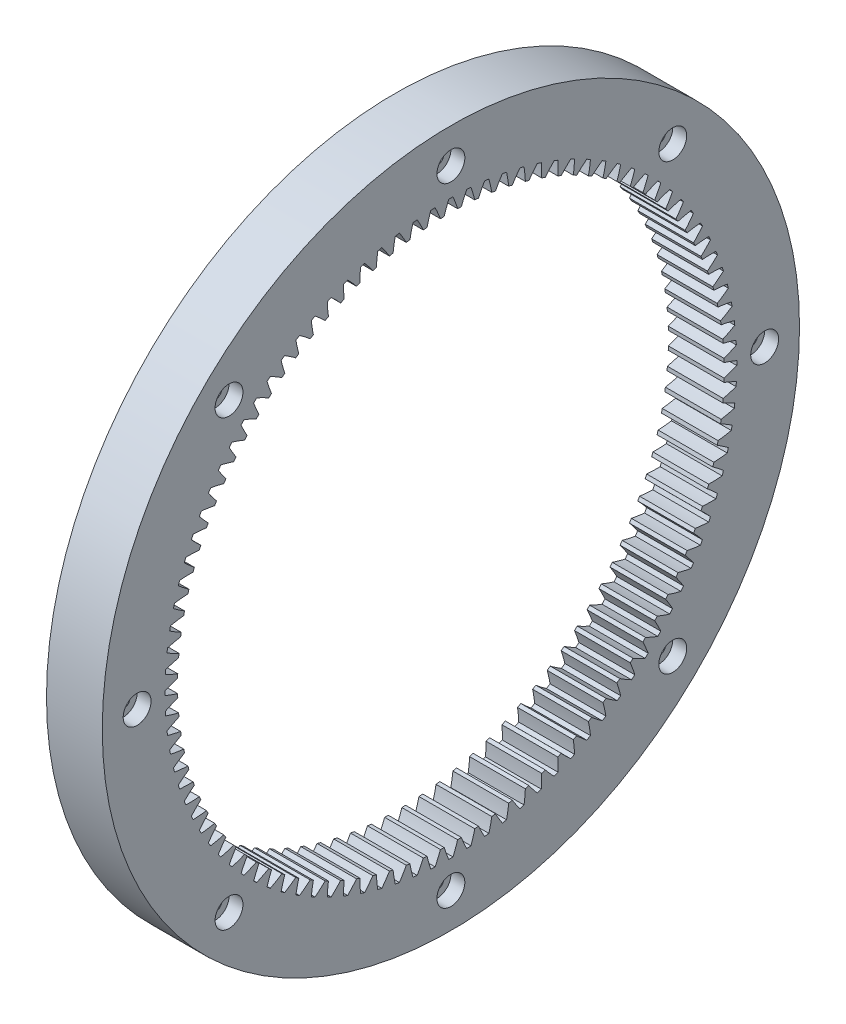
SolidWorks part; units mm, degrees
ref_plane "Front Plane" through (0, 0, 0) normal (0, 0, 1) x (1, 0, 0)
ref_plane "Top Plane" through (0, 0, 0) normal (0, 1, 0) x (1, 0, 0)
ref_plane "Right Plane" through (0, 0, 0) normal (1, 0, 0) x (0, 0, -1)
ref_plane "Plane1" through (-19.2805, 0, 0) normal (-1, 0, 0) x (0, -1, 0)
sketch "Sketch1" plane through (-19.2805, 0, 0) normal (-1, 0, 0) x (0, -1, 0)
  circle A0 centre (2.1716, 9.011) radius 125
  arc A1 (-100.1723, 3.3383) -> (-95.7567, 5.2635) centre (-78.005, -41.4792) cw
  arc A2 (-95.7567, 5.2635) -> (-95.7988, 6.6021) centre (2.1716, 9.011) cw
  arc A3 (-95.7988, 6.6021) -> (-100.3265, 8.2462) centre (-81.0171, 54.3672) cw
  arc A4 (-100.3265, 8.2462) -> (-100.3265, 9.7757) centre (2.1716, 9.011) cw
  arc A5 (-100.3265, 9.7757) -> (-95.7988, 11.4198) centre (-81.0171, -36.3453) cw
  arc A6 (-95.7988, 11.4198) -> (-95.7567, 12.7585) centre (2.1716, 9.011) cw
  arc A7 (-95.7567, 12.7585) -> (-100.1723, 14.6836) centre (-78.005, 59.5012) cw
  arc A8 (-100.1723, 14.6836) -> (-100.0763, 16.2101) centre (2.1716, 9.011) cw
  arc A9 (-100.0763, 16.2101) -> (-95.4542, 17.5667) centre (-83.7009, -31.0323) cw
  arc A10 (-95.4542, 17.5667) -> (-95.3282, 18.9001) centre (2.1716, 9.011) cw
  arc A11 (-95.3282, 18.9001) -> (-99.6142, 21.0987) centre (-74.6765, 64.4359) cw
  arc A12 (-99.6142, 21.0987) -> (-99.4225, 22.6161) centre (2.1716, 9.011) cw
  arc A13 (-99.4225, 22.6161) -> (-94.7244, 23.6798) centre (-86.0458, -25.5613) cw
  arc A14 (-94.7244, 23.6798) -> (-94.5148, 25.0026) centre (2.1716, 9.011) cw
  arc A15 (-94.5148, 25.0026) -> (-98.6543, 27.466) centre (-71.0447, 69.1518) cw
  arc A16 (-98.6543, 27.466) -> (-98.3677, 28.9684) centre (2.1716, 9.011) cw
  arc A17 (-98.3677, 28.9684) -> (-93.6121, 29.735) centre (-88.0425, -19.9539) cw
  arc A18 (-93.6121, 29.735) -> (-93.3199, 31.0421) centre (2.1716, 9.011) cw
  arc A19 (-93.3199, 31.0421) -> (-97.2966, 33.7605) centre (-67.1239, 73.6304) cw
  arc A20 (-97.2966, 33.7605) -> (-96.9162, 35.242) centre (2.1716, 9.011) cw
  arc A21 (-96.9162, 35.242) -> (-92.1218, 35.7084) centre (-89.6832, -14.2321) cw
  arc A22 (-92.1218, 35.7084) -> (-91.7481, 36.9945) centre (2.1716, 9.011) cw
  arc A23 (-91.7481, 36.9945) -> (-95.5462, 39.9573) centre (-62.9297, 77.854) cw
  arc A24 (-95.5462, 39.9573) -> (-95.0736, 41.412) centre (2.1716, 9.011) cw
  arc A25 (-95.0736, 41.412) -> (-90.2594, 41.5764) centre (-90.9614, -8.4186) cw
  arc A26 (-90.2594, 41.5764) -> (-89.8057, 42.8366) centre (2.1716, 9.011) cw
  arc A27 (-89.8057, 42.8366) -> (-93.4103, 46.032) centre (-58.4786, 81.8059) cw
  arc A28 (-93.4103, 46.032) -> (-92.8472, 47.4541) centre (2.1716, 9.011) cw
  arc A29 (-92.8472, 47.4541) -> (-88.0322, 47.316) centre (-91.872, -2.5364) cw
  arc A30 (-88.0322, 47.316) -> (-87.5003, 48.5452) centre (2.1716, 9.011) cw
  arc A31 (-87.5003, 48.5452) -> (-90.8971, 51.9606) centre (-53.788, 85.4705) cw
  arc A32 (-90.8971, 51.9606) -> (-90.2459, 53.3445) centre (2.1716, 9.011) cw
  arc A33 (-90.2459, 53.3445) -> (-85.449, 52.9043) centre (-92.4115, 3.3915) cw
  arc A34 (-85.449, 52.9043) -> (-84.841, 54.0977) centre (2.1716, 9.011) cw
  arc A35 (-84.841, 54.0977) -> (-88.0166, 57.7197) centre (-48.8767, 88.8334) cw
  arc A36 (-88.0166, 57.7197) -> (-87.2798, 59.06) centre (2.1716, 9.011) cw
  arc A37 (-87.2798, 59.06) -> (-82.52, 58.3195) centre (-92.5777, 9.3415) cw
  arc A38 (-82.52, 58.3195) -> (-81.8383, 59.4723) centre (2.1716, 9.011) cw
  arc A39 (-81.8383, 59.4723) -> (-84.7802, 63.2865) centre (-43.7639, 91.8812) cw
  arc A40 (-84.7802, 63.2865) -> (-83.9607, 64.5779) centre (2.1716, 9.011) cw
  arc A41 (-83.9607, 64.5779) -> (-79.2568, 63.54) centre (-92.37, 15.2902) cw
  arc A42 (-79.2568, 63.54) -> (-78.504, 64.6477) centre (2.1716, 9.011) cw
  arc A43 (-78.504, 64.6477) -> (-81.2007, 68.6392) centre (-38.4698, 94.602) cw
  arc A44 (-81.2007, 68.6392) -> (-80.3016, 69.8766) centre (2.1716, 9.011) cw
  arc A45 (-80.3016, 69.8766) -> (-75.6722, 68.5453) centre (-91.7892, 21.2141) cw
  arc A46 (-75.6722, 68.5453) -> (-74.8513, 69.6036) centre (2.1716, 9.011) cw
  arc A47 (-74.8513, 69.6036) -> (-77.292, 73.7565) centre (-33.0152, 96.985) cw
  arc A48 (-77.292, 73.7565) -> (-76.3171, 74.935) centre (2.1716, 9.011) cw
  arc A49 (-76.3171, 74.935) -> (-71.7804, 73.3157) centre (-90.8375, 27.0899) cw
  arc A50 (-71.7804, 73.3157) -> (-70.8947, 74.3204) centre (2.1716, 9.011) cw
  arc A51 (-70.8947, 74.3204) -> (-73.0698, 78.6183) centre (-27.4219, 99.0208) cw
  arc A52 (-73.0698, 78.6183) -> (-72.0228, 79.7333) centre (2.1716, 9.011) cw
  arc A53 (-72.0228, 79.7333) -> (-67.5968, 77.8323) centre (-89.5188, 32.8943) cw
  arc A54 (-67.5968, 77.8323) -> (-66.6497, 78.7794) centre (2.1716, 9.011) cw
  arc A55 (-66.6497, 78.7794) -> (-68.5507, 83.2054) centre (-21.7117, 100.7014) cw
  arc A56 (-68.5507, 83.2054) -> (-67.4357, 84.2524) centre (2.1716, 9.011) cw
  arc A57 (-67.4357, 84.2524) -> (-63.1378, 82.0773) centre (-87.8383, 38.6045) cw
  arc A58 (-63.1378, 82.0773) -> (-62.1331, 82.963) centre (2.1716, 9.011) cw
  arc A59 (-62.1331, 82.963) -> (-63.7524, 87.4997) centre (-15.9073, 102.0201) cw
  arc A60 (-63.7524, 87.4997) -> (-62.5739, 88.4746) centre (2.1716, 9.011) cw
  arc A61 (-62.5739, 88.4746) -> (-58.421, 86.0339) centre (-85.8024, 44.1978) cw
  arc A62 (-58.421, 86.0339) -> (-57.3627, 86.8548) centre (2.1716, 9.011) cw
  arc A63 (-57.3627, 86.8548) -> (-58.694, 91.4842) centre (-10.0315, 102.9718) cw
  arc A64 (-58.694, 91.4842) -> (-57.4566, 92.3832) centre (2.1716, 9.011) cw
  arc A65 (-57.4566, 92.3832) -> (-53.4652, 89.6866) centre (-83.4195, 49.6523) cw
  arc A66 (-53.4652, 89.6866) -> (-52.3574, 90.4394) centre (2.1716, 9.011) cw
  arc A67 (-52.3574, 90.4394) -> (-53.3954, 95.1432) centre (-4.1076, 103.5526) cw
  arc A68 (-53.3954, 95.1432) -> (-52.1039, 95.9628) centre (2.1716, 9.011) cw
  arc A69 (-52.1039, 95.9628) -> (-48.2897, 93.0208) centre (-80.6987, 54.9464) cw
  arc A70 (-48.2897, 93.0208) -> (-47.1369, 93.7026) centre (2.1716, 9.011) cw
  arc A71 (-47.1369, 93.7026) -> (-47.8774, 98.4624) centre (1.8411, 103.7603) cw
  arc A72 (-47.8774, 98.4624) -> (-46.5371, 99.1992) centre (2.1716, 9.011) cw
  arc A73 (-46.5371, 99.1992) -> (-42.9151, 96.0236) centre (-77.6508, 60.0593) cw
  arc A74 (-42.9151, 96.0236) -> (-41.7217, 96.6316) centre (2.1716, 9.011) cw
  arc A75 (-41.7217, 96.6316) -> (-42.162, 101.4285) centre (7.7911, 103.5941) cw
  arc A76 (-42.162, 101.4285) -> (-40.778, 102.0797) centre (2.1716, 9.011) cw
  arc A77 (-40.778, 102.0797) -> (-37.3626, 98.6829) centre (-74.288, 64.9706) cw
  arc A78 (-37.3626, 98.6829) -> (-36.1334, 99.2148) centre (2.1716, 9.011) cw
  arc A79 (-36.1334, 99.2148) -> (-36.2715, 104.0298) centre (13.719, 103.0546) cw
  arc A80 (-36.2715, 104.0298) -> (-34.8494, 104.5929) centre (2.1716, 9.011) cw
  arc A81 (-34.8494, 104.5929) -> (-31.654, 100.9883) centre (-70.6234, 69.6611) cw
  arc A82 (-31.654, 100.9883) -> (-30.3939, 101.442) centre (2.1716, 9.011) cw
  arc A83 (-30.3939, 101.442) -> (-30.2294, 106.2562) centre (19.6012, 102.144) cw
  arc A84 (-30.2294, 106.2562) -> (-28.7747, 106.7288) centre (2.1716, 9.011) cw
  arc A85 (-28.7747, 106.7288) -> (-25.812, 102.9307) centre (-66.6715, 74.1123) cw
  arc A86 (-25.812, 102.9307) -> (-24.5258, 103.3044) centre (2.1716, 9.011) cw
  arc A87 (-24.5258, 103.3044) -> (-24.0594, 108.0988) centre (25.4147, 100.8658) cw
  arc A88 (-24.0594, 108.0988) -> (-22.5779, 108.4791) centre (2.1716, 9.011) cw
  arc A89 (-22.5779, 108.4791) -> (-19.8595, 104.5025) centre (-62.4479, 78.3065) cw
  arc A90 (-19.8595, 104.5025) -> (-18.5524, 104.7947) centre (2.1716, 9.011) cw
  arc A91 (-18.5524, 104.7947) -> (-17.7858, 109.5503) centre (31.1364, 99.2251) cw
  arc A92 (-17.7858, 109.5503) -> (-16.2834, 109.8369) centre (2.1716, 9.011) cw
  arc A93 (-16.2834, 109.8369) -> (-13.82, 105.6974) centre (-57.9693, 82.2273) cw
  arc A94 (-13.82, 105.6974) -> (-12.4972, 105.9069) centre (2.1716, 9.011) cw
  arc A95 (-12.4972, 105.9069) -> (-11.4335, 110.605) centre (36.7439, 97.2284) cw
  arc A96 (-11.4335, 110.605) -> (-9.9161, 110.7967) centre (2.1716, 9.011) cw
  arc A97 (-9.9161, 110.7967) -> (-7.7175, 106.5107) centre (-53.2533, 85.8591) cw
  arc A98 (-7.7175, 106.5107) -> (-6.3841, 106.6368) centre (2.1716, 9.011) cw
  arc A99 (-6.3841, 106.6368) -> (-5.0276, 111.2588) centre (42.2149, 94.8835) cw
  arc A100 (-5.0276, 111.2588) -> (-3.5011, 111.3549) centre (2.1716, 9.011) cw
  arc A101 (-3.5011, 111.3549) -> (-1.5759, 106.9393) centre (-48.3186, 89.1876) cw
  arc A102 (-1.5759, 106.9393) -> (-0.2372, 106.9814) centre (2.1716, 9.011) cw
  arc A103 (-0.2372, 106.9814) -> (1.4068, 111.5091) centre (47.5278, 92.1997) cw
  arc A104 (1.4068, 111.5091) -> (2.9364, 111.5091) centre (2.1716, 9.011) cw
  arc A105 (2.9364, 111.5091) -> (4.5804, 106.9814) centre (-43.1846, 92.1997) cw
  arc A106 (4.5804, 106.9814) -> (5.9191, 106.9393) centre (2.1716, 9.011) cw
  arc A107 (5.9191, 106.9393) -> (7.8443, 111.3549) centre (52.6618, 89.1876) cw
  arc A108 (7.8443, 111.3549) -> (9.3708, 111.2588) centre (2.1716, 9.011) cw
  arc A109 (9.3708, 111.2588) -> (10.7273, 106.6368) centre (-37.8717, 94.8835) cw
  arc A110 (10.7273, 106.6368) -> (12.0607, 106.5107) centre (2.1716, 9.011) cw
  arc A111 (12.0607, 106.5107) -> (14.2593, 110.7967) centre (57.5965, 85.8591) cw
  arc A112 (14.2593, 110.7967) -> (15.7768, 110.605) centre (2.1716, 9.011) cw
  arc A113 (15.7768, 110.605) -> (16.8404, 105.9069) centre (-32.4007, 97.2284) cw
  arc A114 (16.8404, 105.9069) -> (18.1633, 105.6974) centre (2.1716, 9.011) cw
  arc A115 (18.1633, 105.6974) -> (20.6266, 109.8369) centre (62.3125, 82.2273) cw
  arc A116 (20.6266, 109.8369) -> (22.1291, 109.5503) centre (2.1716, 9.011) cw
  arc A117 (22.1291, 109.5503) -> (22.8956, 104.7947) centre (-26.7932, 99.2251) cw
  arc A118 (22.8956, 104.7947) -> (24.2027, 104.5025) centre (2.1716, 9.011) cw
  arc A119 (24.2027, 104.5025) -> (26.9211, 108.4791) centre (66.7911, 78.3065) cw
  arc A120 (26.9211, 108.4791) -> (28.4026, 108.0988) centre (2.1716, 9.011) cw
  arc A121 (28.4026, 108.0988) -> (28.869, 103.3044) centre (-21.0715, 100.8658) cw
  arc A122 (28.869, 103.3044) -> (30.1552, 102.9307) centre (2.1716, 9.011) cw
  arc A123 (30.1552, 102.9307) -> (33.1179, 106.7288) centre (71.0147, 74.1123) cw
  arc A124 (33.1179, 106.7288) -> (34.5726, 106.2562) centre (2.1716, 9.011) cw
  arc A125 (34.5726, 106.2562) -> (34.7371, 101.442) centre (-15.258, 102.144) cw
  arc A126 (34.7371, 101.442) -> (35.9972, 100.9883) centre (2.1716, 9.011) cw
  arc A127 (35.9972, 100.9883) -> (39.1926, 104.5929) centre (74.9666, 69.6611) cw
  arc A128 (39.1926, 104.5929) -> (40.6147, 104.0298) centre (2.1716, 9.011) cw
  arc A129 (40.6147, 104.0298) -> (40.4766, 99.2148) centre (-9.3757, 103.0546) cw
  arc A130 (40.4766, 99.2148) -> (41.7058, 98.6829) centre (2.1716, 9.011) cw
  arc A131 (41.7058, 98.6829) -> (45.1212, 102.0797) centre (78.6312, 64.9706) cw
  arc A132 (45.1212, 102.0797) -> (46.5052, 101.4285) centre (2.1716, 9.011) cw
  arc A133 (46.5052, 101.4285) -> (46.065, 96.6316) centre (-3.4479, 103.5941) cw
  arc A134 (46.065, 96.6316) -> (47.2583, 96.0236) centre (2.1716, 9.011) cw
  arc A135 (47.2583, 96.0236) -> (50.8803, 99.1992) centre (81.994, 60.0593) cw
  arc A136 (50.8803, 99.1992) -> (52.2206, 98.4624) centre (2.1716, 9.011) cw
  arc A137 (52.2206, 98.4624) -> (51.4801, 93.7026) centre (2.5021, 103.7603) cw
  arc A138 (51.4801, 93.7026) -> (52.6329, 93.0208) centre (2.1716, 9.011) cw
  arc A139 (52.6329, 93.0208) -> (56.4472, 95.9628) centre (85.0419, 54.9464) cw
  arc A140 (56.4472, 95.9628) -> (57.7386, 95.1432) centre (2.1716, 9.011) cw
  arc A141 (57.7386, 95.1432) -> (56.7006, 90.4394) centre (8.4508, 103.5526) cw
  arc A142 (56.7006, 90.4394) -> (57.8084, 89.6866) centre (2.1716, 9.011) cw
  arc A143 (57.8084, 89.6866) -> (61.7998, 92.3832) centre (87.7627, 49.6523) cw
  arc A144 (61.7998, 92.3832) -> (63.0372, 91.4842) centre (2.1716, 9.011) cw
  arc A145 (63.0372, 91.4842) -> (61.7059, 86.8548) centre (14.3747, 102.9718) cw
  arc A146 (61.7059, 86.8548) -> (62.7642, 86.0339) centre (2.1716, 9.011) cw
  arc A147 (62.7642, 86.0339) -> (66.9171, 88.4746) centre (90.1457, 44.1978) cw
  arc A148 (66.9171, 88.4746) -> (68.0956, 87.4997) centre (2.1716, 9.011) cw
  arc A149 (68.0956, 87.4997) -> (66.4763, 82.963) centre (20.2505, 102.0201) cw
  arc A150 (66.4763, 82.963) -> (67.481, 82.0773) centre (2.1716, 9.011) cw
  arc A151 (67.481, 82.0773) -> (71.7789, 84.2524) centre (92.1815, 38.6045) cw
  arc A152 (71.7789, 84.2524) -> (72.8939, 83.2054) centre (2.1716, 9.011) cw
  arc A153 (72.8939, 83.2054) -> (70.9929, 78.7794) centre (26.0549, 100.7014) cw
  arc A154 (70.9929, 78.7794) -> (71.94, 77.8323) centre (2.1716, 9.011) cw
  arc A155 (71.94, 77.8323) -> (76.366, 79.7333) centre (93.862, 32.8943) cw
  arc A156 (76.366, 79.7333) -> (77.4131, 78.6183) centre (2.1716, 9.011) cw
  arc A157 (77.4131, 78.6183) -> (75.2379, 74.3204) centre (31.7651, 99.0208) cw
  arc A158 (75.2379, 74.3204) -> (76.1236, 73.3157) centre (2.1716, 9.011) cw
  arc A159 (76.1236, 73.3157) -> (80.6603, 74.935) centre (95.1808, 27.0899) cw
  arc A160 (80.6603, 74.935) -> (81.6353, 73.7565) centre (2.1716, 9.011) cw
  arc A161 (81.6353, 73.7565) -> (79.1945, 69.6036) centre (37.3585, 96.985) cw
  arc A162 (79.1945, 69.6036) -> (80.0154, 68.5453) centre (2.1716, 9.011) cw
  arc A163 (80.0154, 68.5453) -> (84.6448, 69.8766) centre (96.1324, 21.2141) cw
  arc A164 (84.6448, 69.8766) -> (85.5439, 68.6392) centre (2.1716, 9.011) cw
  arc A165 (85.5439, 68.6392) -> (82.8472, 64.6477) centre (42.813, 94.602) cw
  arc A166 (82.8472, 64.6477) -> (83.6, 63.54) centre (2.1716, 9.011) cw
  arc A167 (83.6, 63.54) -> (88.3039, 64.5779) centre (96.7132, 15.2902) cw
  arc A168 (88.3039, 64.5779) -> (89.1234, 63.2865) centre (2.1716, 9.011) cw
  arc A169 (89.1234, 63.2865) -> (86.1815, 59.4723) centre (48.1071, 91.8812) cw
  arc A170 (86.1815, 59.4723) -> (86.8632, 58.3195) centre (2.1716, 9.011) cw
  arc A171 (86.8632, 58.3195) -> (91.623, 59.06) centre (96.921, 9.3415) cw
  arc A172 (91.623, 59.06) -> (92.3598, 57.7197) centre (2.1716, 9.011) cw
  arc A173 (92.3598, 57.7197) -> (89.1842, 54.0977) centre (53.2199, 88.8334) cw
  arc A174 (89.1842, 54.0977) -> (89.7922, 52.9043) centre (2.1716, 9.011) cw
  arc A175 (89.7922, 52.9043) -> (94.5891, 53.3445) centre (96.7547, 3.3915) cw
  arc A176 (94.5891, 53.3445) -> (95.2403, 51.9606) centre (2.1716, 9.011) cw
  arc A177 (95.2403, 51.9606) -> (91.8435, 48.5452) centre (58.1313, 85.4705) cw
  arc A178 (91.8435, 48.5452) -> (92.3754, 47.316) centre (2.1716, 9.011) cw
  arc A179 (92.3754, 47.316) -> (97.1904, 47.4541) centre (96.2153, -2.5364) cw
  arc A180 (97.1904, 47.4541) -> (97.7535, 46.032) centre (2.1716, 9.011) cw
  arc A181 (97.7535, 46.032) -> (94.1489, 42.8366) centre (62.8218, 81.8059) cw
  arc A182 (94.1489, 42.8366) -> (94.6026, 41.5764) centre (2.1716, 9.011) cw
  arc A183 (94.6026, 41.5764) -> (99.4168, 41.412) centre (95.3046, -8.4186) cw
  arc A184 (99.4168, 41.412) -> (99.8895, 39.9573) centre (2.1716, 9.011) cw
  arc A185 (99.8895, 39.9573) -> (96.0914, 36.9945) centre (67.2729, 77.854) cw
  arc A186 (96.0914, 36.9945) -> (96.465, 35.7084) centre (2.1716, 9.011) cw
  arc A187 (96.465, 35.7084) -> (101.2594, 35.242) centre (94.0264, -14.2321) cw
  arc A188 (101.2594, 35.242) -> (101.6398, 33.7605) centre (2.1716, 9.011) cw
  arc A189 (101.6398, 33.7605) -> (97.6631, 31.0421) centre (71.4672, 73.6304) cw
  arc A190 (97.6631, 31.0421) -> (97.9553, 29.735) centre (2.1716, 9.011) cw
  arc A191 (97.9553, 29.735) -> (102.7109, 28.9684) centre (92.3857, -19.9539) cw
  arc A192 (102.7109, 28.9684) -> (102.9975, 27.466) centre (2.1716, 9.011) cw
  arc A193 (102.9975, 27.466) -> (98.858, 25.0026) centre (75.3879, 69.1518) cw
  arc A194 (98.858, 25.0026) -> (99.0676, 23.6798) centre (2.1716, 9.011) cw
  arc A195 (99.0676, 23.6798) -> (103.7657, 22.6161) centre (90.389, -25.5613) cw
  arc A196 (103.7657, 22.6161) -> (103.9574, 21.0987) centre (2.1716, 9.011) cw
  arc A197 (103.9574, 21.0987) -> (99.6714, 18.9001) centre (79.0197, 64.4359) cw
  arc A198 (99.6714, 18.9001) -> (99.7974, 17.5667) centre (2.1716, 9.011) cw
  arc A199 (99.7974, 17.5667) -> (104.4195, 16.2101) centre (88.0441, -31.0323) cw
  arc A200 (104.4195, 16.2101) -> (104.5155, 14.6836) centre (2.1716, 9.011) cw
  arc A201 (104.5155, 14.6836) -> (100.0999, 12.7585) centre (82.3482, 59.5012) cw
  arc A202 (100.0999, 12.7585) -> (100.142, 11.4198) centre (2.1716, 9.011) cw
  arc A203 (100.142, 11.4198) -> (104.6698, 9.7757) centre (85.3603, -36.3453) cw
  arc A204 (104.6698, 9.7757) -> (104.6698, 8.2462) centre (2.1716, 9.011) cw
  arc A205 (104.6698, 8.2462) -> (100.142, 6.6021) centre (85.3603, 54.3672) cw
  arc A206 (100.142, 6.6021) -> (100.0999, 5.2635) centre (2.1716, 9.011) cw
  arc A207 (100.0999, 5.2635) -> (104.5155, 3.3383) centre (82.3482, -41.4792) cw
  arc A208 (104.5155, 3.3383) -> (104.4195, 1.8118) centre (2.1716, 9.011) cw
  arc A209 (104.4195, 1.8118) -> (99.7974, 0.4553) centre (88.0441, 49.0542) cw
  arc A210 (99.7974, 0.4553) -> (99.6714, -0.8781) centre (2.1716, 9.011) cw
  arc A211 (99.6714, -0.8781) -> (103.9574, -3.0767) centre (79.0197, -46.4139) cw
  arc A212 (103.9574, -3.0767) -> (103.7657, -4.5942) centre (2.1716, 9.011) cw
  arc A213 (103.7657, -4.5942) -> (99.0676, -5.6578) centre (90.389, 43.5832) cw
  arc A214 (99.0676, -5.6578) -> (98.858, -6.9807) centre (2.1716, 9.011) cw
  arc A215 (98.858, -6.9807) -> (102.9975, -9.444) centre (75.3879, -51.1299) cw
  arc A216 (102.9975, -9.444) -> (102.7109, -10.9465) centre (2.1716, 9.011) cw
  arc A217 (102.7109, -10.9465) -> (97.9553, -11.713) centre (92.3857, 37.9758) cw
  arc A218 (97.9553, -11.713) -> (97.6631, -13.0201) centre (2.1716, 9.011) cw
  arc A219 (97.6631, -13.0201) -> (101.6398, -15.7385) centre (71.4672, -55.6085) cw
  arc A220 (101.6398, -15.7385) -> (101.2594, -17.22) centre (2.1716, 9.011) cw
  arc A221 (101.2594, -17.22) -> (96.465, -17.6864) centre (94.0264, 32.2541) cw
  arc A222 (96.465, -17.6864) -> (96.0914, -18.9726) centre (2.1716, 9.011) cw
  arc A223 (96.0914, -18.9726) -> (99.8895, -21.9354) centre (67.2729, -59.8321) cw
  arc A224 (99.8895, -21.9354) -> (99.4168, -23.39) centre (2.1716, 9.011) cw
  arc A225 (99.4168, -23.39) -> (94.6026, -23.5545) centre (95.3046, 26.4406) cw
  arc A226 (94.6026, -23.5545) -> (94.1489, -24.8146) centre (2.1716, 9.011) cw
  arc A227 (94.1489, -24.8146) -> (97.7535, -28.0101) centre (62.8218, -63.784) cw
  arc A228 (97.7535, -28.0101) -> (97.1904, -29.4322) centre (2.1716, 9.011) cw
  arc A229 (97.1904, -29.4322) -> (92.3754, -29.294) centre (96.2153, 20.5583) cw
  arc A230 (92.3754, -29.294) -> (91.8435, -30.5232) centre (2.1716, 9.011) cw
  arc A231 (91.8435, -30.5232) -> (95.2403, -33.9386) centre (58.1313, -67.4486) cw
  arc A232 (95.2403, -33.9386) -> (94.5891, -35.3226) centre (2.1716, 9.011) cw
  arc A233 (94.5891, -35.3226) -> (89.7922, -34.8824) centre (96.7547, 14.6305) cw
  arc A234 (89.7922, -34.8824) -> (89.1842, -36.0757) centre (2.1716, 9.011) cw
  arc A235 (89.1842, -36.0757) -> (92.3598, -39.6977) centre (53.2199, -70.8115) cw
  arc A236 (92.3598, -39.6977) -> (91.623, -41.038) centre (2.1716, 9.011) cw
  arc A237 (91.623, -41.038) -> (86.8632, -40.2975) centre (96.921, 8.6805) cw
  arc A238 (86.8632, -40.2975) -> (86.1815, -41.4503) centre (2.1716, 9.011) cw
  arc A239 (86.1815, -41.4503) -> (89.1234, -45.2646) centre (48.1071, -73.8593) cw
  arc A240 (89.1234, -45.2646) -> (88.3039, -46.556) centre (2.1716, 9.011) cw
  arc A241 (88.3039, -46.556) -> (83.6, -45.518) centre (96.7132, 2.7318) cw
  arc A242 (83.6, -45.518) -> (82.8472, -46.6258) centre (2.1716, 9.011) cw
  arc A243 (82.8472, -46.6258) -> (85.5439, -50.6172) centre (42.813, -76.5801) cw
  arc A244 (85.5439, -50.6172) -> (84.6448, -51.8546) centre (2.1716, 9.011) cw
  arc A245 (84.6448, -51.8546) -> (80.0154, -50.5234) centre (96.1324, -3.1922) cw
  arc A246 (80.0154, -50.5234) -> (79.1945, -51.5817) centre (2.1716, 9.011) cw
  arc A247 (79.1945, -51.5817) -> (81.6353, -55.7345) centre (37.3585, -78.9631) cw
  arc A248 (81.6353, -55.7345) -> (80.6603, -56.9131) centre (2.1716, 9.011) cw
  arc A249 (80.6603, -56.9131) -> (76.1236, -55.2937) centre (95.1808, -9.0679) cw
  arc A250 (76.1236, -55.2937) -> (75.2379, -56.2984) centre (2.1716, 9.011) cw
  arc A251 (75.2379, -56.2984) -> (77.4131, -60.5963) centre (31.7651, -80.9989) cw
  arc A252 (77.4131, -60.5963) -> (76.366, -61.7113) centre (2.1716, 9.011) cw
  arc A253 (76.366, -61.7113) -> (71.94, -59.8103) centre (93.862, -14.8723) cw
  arc A254 (71.94, -59.8103) -> (70.9929, -60.7574) centre (2.1716, 9.011) cw
  arc A255 (70.9929, -60.7574) -> (72.8939, -65.1834) centre (26.0549, -82.6795) cw
  arc A256 (72.8939, -65.1834) -> (71.7789, -66.2305) centre (2.1716, 9.011) cw
  arc A257 (71.7789, -66.2305) -> (67.481, -64.0553) centre (92.1815, -20.5825) cw
  arc A258 (67.481, -64.0553) -> (66.4763, -64.9411) centre (2.1716, 9.011) cw
  arc A259 (66.4763, -64.9411) -> (68.0956, -69.4777) centre (20.2505, -83.9982) cw
  arc A260 (68.0956, -69.4777) -> (66.9171, -70.4527) centre (2.1716, 9.011) cw
  arc A261 (66.9171, -70.4527) -> (62.7642, -68.012) centre (90.1457, -26.1759) cw
  arc A262 (62.7642, -68.012) -> (61.7059, -68.8329) centre (2.1716, 9.011) cw
  arc A263 (61.7059, -68.8329) -> (63.0372, -73.4623) centre (14.3747, -84.9498) cw
  arc A264 (63.0372, -73.4623) -> (61.7998, -74.3613) centre (2.1716, 9.011) cw
  arc A265 (61.7998, -74.3613) -> (57.8084, -71.6646) centre (87.7627, -31.6304) cw
  arc A266 (57.8084, -71.6646) -> (56.7006, -72.4174) centre (2.1716, 9.011) cw
  arc A267 (56.7006, -72.4174) -> (57.7386, -77.1213) centre (8.4508, -85.5307) cw
  arc A268 (57.7386, -77.1213) -> (56.4472, -77.9409) centre (2.1716, 9.011) cw
  arc A269 (56.4472, -77.9409) -> (52.6329, -74.9989) centre (85.0419, -36.9245) cw
  arc A270 (52.6329, -74.9989) -> (51.4801, -75.6807) centre (2.1716, 9.011) cw
  arc A271 (51.4801, -75.6807) -> (52.2206, -80.4404) centre (2.5021, -85.7384) cw
  arc A272 (52.2206, -80.4404) -> (50.8803, -81.1773) centre (2.1716, 9.011) cw
  arc A273 (50.8803, -81.1773) -> (47.2583, -78.0016) centre (81.994, -42.0373) cw
  arc A274 (47.2583, -78.0016) -> (46.065, -78.6096) centre (2.1716, 9.011) cw
  arc A275 (46.065, -78.6096) -> (46.5052, -83.4065) centre (-3.4479, -85.5722) cw
  arc A276 (46.5052, -83.4065) -> (45.1212, -84.0577) centre (2.1716, 9.011) cw
  arc A277 (45.1212, -84.0577) -> (41.7058, -80.6609) centre (78.6312, -46.9487) cw
  arc A278 (41.7058, -80.6609) -> (40.4766, -81.1928) centre (2.1716, 9.011) cw
  arc A279 (40.4766, -81.1928) -> (40.6147, -86.0079) centre (-9.3757, -85.0327) cw
  arc A280 (40.6147, -86.0079) -> (39.1926, -86.5709) centre (2.1716, 9.011) cw
  arc A281 (39.1926, -86.5709) -> (35.9972, -82.9663) centre (74.9666, -51.6392) cw
  arc A282 (35.9972, -82.9663) -> (34.7371, -83.42) centre (2.1716, 9.011) cw
  arc A283 (34.7371, -83.42) -> (34.5726, -88.2342) centre (-15.258, -84.122) cw
  arc A284 (34.5726, -88.2342) -> (33.1179, -88.7069) centre (2.1716, 9.011) cw
  arc A285 (33.1179, -88.7069) -> (30.1552, -84.9088) centre (71.0147, -56.0903) cw
  arc A286 (30.1552, -84.9088) -> (28.869, -85.2824) centre (2.1716, 9.011) cw
  arc A287 (28.869, -85.2824) -> (28.4026, -90.0768) centre (-21.0715, -82.8438) cw
  arc A288 (28.4026, -90.0768) -> (26.9211, -90.4572) centre (2.1716, 9.011) cw
  arc A289 (26.9211, -90.4572) -> (24.2027, -86.4805) centre (66.7911, -60.2846) cw
  arc A290 (24.2027, -86.4805) -> (22.8956, -86.7727) centre (2.1716, 9.011) cw
  arc A291 (22.8956, -86.7727) -> (22.1291, -91.5283) centre (-26.7932, -81.2031) cw
  arc A292 (22.1291, -91.5283) -> (20.6266, -91.8149) centre (2.1716, 9.011) cw
  arc A293 (20.6266, -91.8149) -> (18.1633, -87.6755) centre (62.3125, -64.2053) cw
  arc A294 (18.1633, -87.6755) -> (16.8404, -87.885) centre (2.1716, 9.011) cw
  arc A295 (16.8404, -87.885) -> (15.7768, -92.5831) centre (-32.4007, -79.2064) cw
  arc A296 (15.7768, -92.5831) -> (14.2593, -92.7748) centre (2.1716, 9.011) cw
  arc A297 (14.2593, -92.7748) -> (12.0607, -88.4888) centre (57.5965, -67.8371) cw
  arc A298 (12.0607, -88.4888) -> (10.7273, -88.6148) centre (2.1716, 9.011) cw
  arc A299 (10.7273, -88.6148) -> (9.3708, -93.2369) centre (-37.8717, -76.8615) cw
  arc A300 (9.3708, -93.2369) -> (7.8443, -93.3329) centre (2.1716, 9.011) cw
  arc A301 (7.8443, -93.3329) -> (5.9191, -88.9173) centre (52.6618, -71.1656) cw
  arc A302 (5.9191, -88.9173) -> (4.5804, -88.9594) centre (2.1716, 9.011) cw
  arc A303 (4.5804, -88.9594) -> (2.9364, -93.4872) centre (-43.1846, -74.1777) cw
  arc A304 (2.9364, -93.4872) -> (1.4068, -93.4872) centre (2.1716, 9.011) cw
  arc A305 (1.4068, -93.4872) -> (-0.2372, -88.9594) centre (47.5278, -74.1777) cw
  arc A306 (-0.2372, -88.9594) -> (-1.5759, -88.9173) centre (2.1716, 9.011) cw
  arc A307 (-1.5759, -88.9173) -> (-3.5011, -93.3329) centre (-48.3186, -71.1656) cw
  arc A308 (-3.5011, -93.3329) -> (-5.0276, -93.2369) centre (2.1716, 9.011) cw
  arc A309 (-5.0276, -93.2369) -> (-6.3841, -88.6148) centre (42.2149, -76.8615) cw
  arc A310 (-6.3841, -88.6148) -> (-7.7175, -88.4888) centre (2.1716, 9.011) cw
  arc A311 (-7.7175, -88.4888) -> (-9.9161, -92.7748) centre (-53.2533, -67.8371) cw
  arc A312 (-9.9161, -92.7748) -> (-11.4335, -92.5831) centre (2.1716, 9.011) cw
  arc A313 (-11.4335, -92.5831) -> (-12.4972, -87.885) centre (36.7439, -79.2064) cw
  arc A314 (-12.4972, -87.885) -> (-13.82, -87.6755) centre (2.1716, 9.011) cw
  arc A315 (-13.82, -87.6755) -> (-16.2834, -91.8149) centre (-57.9693, -64.2053) cw
  arc A316 (-16.2834, -91.8149) -> (-17.7858, -91.5283) centre (2.1716, 9.011) cw
  arc A317 (-17.7858, -91.5283) -> (-18.5524, -86.7727) centre (31.1364, -81.2031) cw
  arc A318 (-18.5524, -86.7727) -> (-19.8595, -86.4805) centre (2.1716, 9.011) cw
  arc A319 (-19.8595, -86.4805) -> (-22.5779, -90.4572) centre (-62.4479, -60.2846) cw
  arc A320 (-22.5779, -90.4572) -> (-24.0594, -90.0768) centre (2.1716, 9.011) cw
  arc A321 (-24.0594, -90.0768) -> (-24.5258, -85.2824) centre (25.4147, -82.8438) cw
  arc A322 (-24.5258, -85.2824) -> (-25.812, -84.9088) centre (2.1716, 9.011) cw
  arc A323 (-25.812, -84.9088) -> (-28.7747, -88.7069) centre (-66.6715, -56.0903) cw
  arc A324 (-28.7747, -88.7069) -> (-30.2294, -88.2342) centre (2.1716, 9.011) cw
  arc A325 (-30.2294, -88.2342) -> (-30.3939, -83.42) centre (19.6012, -84.122) cw
  arc A326 (-30.3939, -83.42) -> (-31.654, -82.9663) centre (2.1716, 9.011) cw
  arc A327 (-31.654, -82.9663) -> (-34.8494, -86.5709) centre (-70.6234, -51.6392) cw
  arc A328 (-34.8494, -86.5709) -> (-36.2715, -86.0079) centre (2.1716, 9.011) cw
  arc A329 (-36.2715, -86.0079) -> (-36.1334, -81.1928) centre (13.719, -85.0327) cw
  arc A330 (-36.1334, -81.1928) -> (-37.3626, -80.6609) centre (2.1716, 9.011) cw
  arc A331 (-37.3626, -80.6609) -> (-40.778, -84.0577) centre (-74.288, -46.9487) cw
  arc A332 (-40.778, -84.0577) -> (-42.162, -83.4065) centre (2.1716, 9.011) cw
  arc A333 (-42.162, -83.4065) -> (-41.7217, -78.6096) centre (7.7911, -85.5722) cw
  arc A334 (-41.7217, -78.6096) -> (-42.9151, -78.0016) centre (2.1716, 9.011) cw
  arc A335 (-42.9151, -78.0016) -> (-46.5371, -81.1773) centre (-77.6508, -42.0373) cw
  arc A336 (-46.5371, -81.1773) -> (-47.8774, -80.4404) centre (2.1716, 9.011) cw
  arc A337 (-47.8774, -80.4404) -> (-47.1369, -75.6807) centre (1.8411, -85.7384) cw
  arc A338 (-47.1369, -75.6807) -> (-48.2897, -74.9989) centre (2.1716, 9.011) cw
  arc A339 (-48.2897, -74.9989) -> (-52.1039, -77.9409) centre (-80.6987, -36.9245) cw
  arc A340 (-52.1039, -77.9409) -> (-53.3954, -77.1213) centre (2.1716, 9.011) cw
  arc A341 (-53.3954, -77.1213) -> (-52.3574, -72.4174) centre (-4.1076, -85.5307) cw
  arc A342 (-52.3574, -72.4174) -> (-53.4652, -71.6646) centre (2.1716, 9.011) cw
  arc A343 (-53.4652, -71.6646) -> (-57.4566, -74.3613) centre (-83.4195, -31.6304) cw
  arc A344 (-57.4566, -74.3613) -> (-58.694, -73.4623) centre (2.1716, 9.011) cw
  arc A345 (-58.694, -73.4623) -> (-57.3627, -68.8329) centre (-10.0315, -84.9498) cw
  arc A346 (-57.3627, -68.8329) -> (-58.421, -68.012) centre (2.1716, 9.011) cw
  arc A347 (-58.421, -68.012) -> (-62.5739, -70.4527) centre (-85.8024, -26.1759) cw
  arc A348 (-62.5739, -70.4527) -> (-63.7524, -69.4777) centre (2.1716, 9.011) cw
  arc A349 (-63.7524, -69.4777) -> (-62.1331, -64.9411) centre (-15.9073, -83.9982) cw
  arc A350 (-62.1331, -64.9411) -> (-63.1378, -64.0553) centre (2.1716, 9.011) cw
  arc A351 (-63.1378, -64.0553) -> (-67.4357, -66.2305) centre (-87.8383, -20.5825) cw
  arc A352 (-67.4357, -66.2305) -> (-68.5507, -65.1834) centre (2.1716, 9.011) cw
  arc A353 (-68.5507, -65.1834) -> (-66.6497, -60.7574) centre (-21.7117, -82.6795) cw
  arc A354 (-66.6497, -60.7574) -> (-67.5968, -59.8103) centre (2.1716, 9.011) cw
  arc A355 (-67.5968, -59.8103) -> (-72.0228, -61.7113) centre (-89.5188, -14.8723) cw
  arc A356 (-72.0228, -61.7113) -> (-73.0698, -60.5963) centre (2.1716, 9.011) cw
  arc A357 (-73.0698, -60.5963) -> (-70.8947, -56.2984) centre (-27.4219, -80.9989) cw
  arc A358 (-70.8947, -56.2984) -> (-71.7804, -55.2937) centre (2.1716, 9.011) cw
  arc A359 (-71.7804, -55.2937) -> (-76.3171, -56.9131) centre (-90.8375, -9.0679) cw
  arc A360 (-76.3171, -56.9131) -> (-77.292, -55.7345) centre (2.1716, 9.011) cw
  arc A361 (-77.292, -55.7345) -> (-74.8513, -51.5817) centre (-33.0152, -78.9631) cw
  arc A362 (-74.8513, -51.5817) -> (-75.6722, -50.5234) centre (2.1716, 9.011) cw
  arc A363 (-75.6722, -50.5234) -> (-80.3016, -51.8546) centre (-91.7892, -3.1922) cw
  arc A364 (-80.3016, -51.8546) -> (-81.2007, -50.6172) centre (2.1716, 9.011) cw
  arc A365 (-81.2007, -50.6172) -> (-78.504, -46.6258) centre (-38.4698, -76.5801) cw
  arc A366 (-78.504, -46.6258) -> (-79.2568, -45.518) centre (2.1716, 9.011) cw
  arc A367 (-79.2568, -45.518) -> (-83.9607, -46.556) centre (-92.37, 2.7318) cw
  arc A368 (-83.9607, -46.556) -> (-84.7802, -45.2646) centre (2.1716, 9.011) cw
  arc A369 (-84.7802, -45.2646) -> (-81.8383, -41.4503) centre (-43.7639, -73.8593) cw
  arc A370 (-81.8383, -41.4503) -> (-82.52, -40.2975) centre (2.1716, 9.011) cw
  arc A371 (-82.52, -40.2975) -> (-87.2798, -41.038) centre (-92.5777, 8.6805) cw
  arc A372 (-87.2798, -41.038) -> (-88.0166, -39.6977) centre (2.1716, 9.011) cw
  arc A373 (-88.0166, -39.6977) -> (-84.841, -36.0757) centre (-48.8767, -70.8115) cw
  arc A374 (-84.841, -36.0757) -> (-85.449, -34.8824) centre (2.1716, 9.011) cw
  arc A375 (-85.449, -34.8824) -> (-90.2459, -35.3226) centre (-92.4115, 14.6305) cw
  arc A376 (-90.2459, -35.3226) -> (-90.8971, -33.9386) centre (2.1716, 9.011) cw
  arc A377 (-90.8971, -33.9386) -> (-87.5003, -30.5232) centre (-53.788, -67.4486) cw
  arc A378 (-87.5003, -30.5232) -> (-88.0322, -29.294) centre (2.1716, 9.011) cw
  arc A379 (-88.0322, -29.294) -> (-92.8472, -29.4322) centre (-91.872, 20.5583) cw
  arc A380 (-92.8472, -29.4322) -> (-93.4103, -28.0101) centre (2.1716, 9.011) cw
  arc A381 (-93.4103, -28.0101) -> (-89.8057, -24.8146) centre (-58.4786, -63.784) cw
  arc A382 (-89.8057, -24.8146) -> (-90.2594, -23.5545) centre (2.1716, 9.011) cw
  arc A383 (-90.2594, -23.5545) -> (-95.0736, -23.39) centre (-90.9614, 26.4406) cw
  arc A384 (-95.0736, -23.39) -> (-95.5462, -21.9354) centre (2.1716, 9.011) cw
  arc A385 (-95.5462, -21.9354) -> (-91.7481, -18.9726) centre (-62.9297, -59.8321) cw
  arc A386 (-91.7481, -18.9726) -> (-92.1218, -17.6864) centre (2.1716, 9.011) cw
  arc A387 (-92.1218, -17.6864) -> (-96.9162, -17.22) centre (-89.6832, 32.2541) cw
  arc A388 (-96.9162, -17.22) -> (-97.2966, -15.7385) centre (2.1716, 9.011) cw
  arc A389 (-97.2966, -15.7385) -> (-93.3199, -13.0201) centre (-67.1239, -55.6085) cw
  arc A390 (-93.3199, -13.0201) -> (-93.6121, -11.713) centre (2.1716, 9.011) cw
  arc A391 (-93.6121, -11.713) -> (-98.3677, -10.9465) centre (-88.0425, 37.9758) cw
  arc A392 (-98.3677, -10.9465) -> (-98.6543, -9.444) centre (2.1716, 9.011) cw
  arc A393 (-98.6543, -9.444) -> (-94.5148, -6.9807) centre (-71.0447, -51.1299) cw
  arc A394 (-94.5148, -6.9807) -> (-94.7244, -5.6578) centre (2.1716, 9.011) cw
  arc A395 (-94.7244, -5.6578) -> (-99.4225, -4.5942) centre (-86.0458, 43.5832) cw
  arc A396 (-99.4225, -4.5942) -> (-99.6142, -3.0767) centre (2.1716, 9.011) cw
  arc A397 (-99.6142, -3.0767) -> (-95.3282, -0.8781) centre (-74.6765, -46.4139) cw
  arc A398 (-95.3282, -0.8781) -> (-95.4542, 0.4553) centre (2.1716, 9.011) cw
  arc A399 (-95.4542, 0.4553) -> (-100.0763, 1.8118) centre (-83.7009, 49.0542) cw
  arc A400 (-100.0763, 1.8118) -> (-100.1723, 3.3383) centre (2.1716, 9.011) cw
extrude "Boss-Extrude1" add sketch "Sketch1" against normal blind 20
sketch "Sketch2" plane through (-19.2805, 0, 0) normal (-1, 0, 0) x (0, 0, 1)
  circle A0 centre (9.011, -2.1716) radius 112.5 construction
  circle A1 centre (88.5605, 77.3779) radius 2.5
  circle A2 centre (121.511, -2.1716) radius 2.5
  circle A3 centre (9.011, -2.1716) radius 125 construction
  circle A4 centre (9.011, 110.3284) radius 2.5
  circle A5 centre (88.5605, -81.7211) radius 2.5
  circle A6 centre (9.011, -114.6716) radius 2.5
  circle A7 centre (-70.5385, -81.7211) radius 2.5
  circle A8 centre (-103.489, -2.1716) radius 2.5
  circle A9 centre (-70.5385, 77.3779) radius 2.5
  point P23 (9.011, -2.1716)
  dimension "D1" = 225
  dimension "D2" = 5
  dimension "D3" = 8
extrude "Cut-Extrude1" cut sketch "Sketch2" against normal blind 20
sketch "Sketch3" plane through (0.7195, 0, 0) normal (1, 0, 0) x (0, 0, -1)
  circle A0 centre (-9.011, 110.3284) radius 5
  circle A1 centre (-9.011, -2.1716) radius 112.5 construction
  circle A2 centre (-9.011, -2.1716) radius 125 construction
  circle A3 centre (70.5385, 77.3779) radius 5
  circle A4 centre (103.489, -2.1716) radius 5
  circle A5 centre (70.5385, -81.7211) radius 5
  circle A6 centre (-9.011, -114.6716) radius 5
  circle A7 centre (-88.5605, -81.7211) radius 5
  circle A8 centre (-121.511, -2.1716) radius 5
  circle A9 centre (-88.5605, 77.3779) radius 5
  point P24 (-9.011, -2.1716)
  dimension "D1" = 10
  dimension "D2" = 8
extrude "Cut-Extrude2" cut sketch "Sketch3" against normal blind 5
